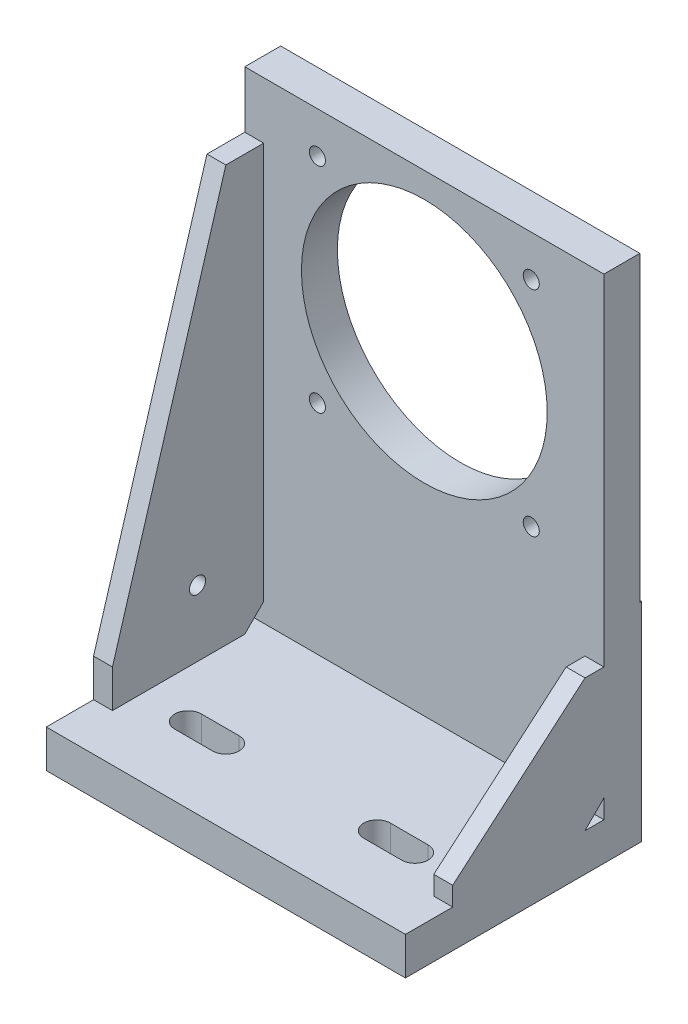
SolidWorks part; units mm, degrees
ref_plane "Front" through (0, 0, 0) normal (0, 0, 1) x (1, 0, 0)
ref_plane "Top" through (0, 0, 0) normal (0, 1, 0) x (1, 0, 0)
ref_plane "Right" through (0, 0, 0) normal (1, 0, 0) x (0, 0, -1)
sketch "Sketch1" plane through (0, 0, 0) normal (0, 1, 0) x (1, 0, 0)
  line L1 (0, 0) -> (190, 0)
  line L2 (0, 0) -> (0, -125)
  line L3 (0, -125) -> (190, -125)
  line L4 (190, 0) -> (190, -125)
  dimension "D1" = 190
  dimension "D2" = 125
extrude "Boss-Extrude1" add sketch "Sketch1" along normal blind 20
sketch "Sketch2" plane through (0, 0, 0) normal (0, 0, -1) x (-1, 0, 0)
  line L0 (-190, 0) -> (0, 0) construction
  line L1 (0, 20) -> (-190, 20)
  line L2 (0, 20) -> (0, 270)
  line L3 (0, 270) -> (-190, 270)
  line L4 (-190, 20) -> (-190, 270)
  dimension "D1" = 270
extrude "Boss-Extrude2" add sketch "Sketch2" against normal blind 20
sketch "Sketch3" plane through (0, 0, 0) normal (-1, 0, 0) x (0, 0, 1)
  line L1 (20, 20) -> (100, 20)
  line L2 (20, 20) -> (20, 240)
  line L3 (20, 240) -> (100, 240)
  line L4 (100, 20) -> (100, 240)
  dimension "D1" = 80
  dimension "D2" = 220
extrude "Boss-Extrude3" add sketch "Sketch3" against normal blind 10
sketch "Sketch4" plane through (190, 0, 0) normal (1, 0, 0) x (0, 0, -1)
  line L1 (-20, 20) -> (-100, 20)
  line L2 (-20, 20) -> (-20, 90)
  line L3 (-20, 90) -> (-100, 90)
  line L4 (-100, 20) -> (-100, 90)
  dimension "D1" = 80
  dimension "D2" = 70
extrude "Boss-Extrude4" add sketch "Sketch4" against normal blind 10
sketch "Sketch5" plane through (0, 0, 0) normal (-1, 0, 0) x (0, 0, 1)
  line L0 (20, 30) -> (20, 20)
  line L1 (20, 20) -> (30, 20)
  line L2 (30, 20) -> (20, 30)
  line L3 (20, 20) -> (100, 20) construction
  line L4 (20, 240) -> (20, 20) construction
  dimension "D1" = 10
extrude "Cut-Extrude1" cut sketch "Sketch5" against normal through all
sketch "Sketch6" plane through (0, 0, 0) normal (-1, 0, 0) x (0, 0, 1)
  line L0 (40, 240) -> (100, 40)
  line L1 (100, 240) -> (20, 240) construction
  line L2 (100, 20) -> (100, 240) construction
  line L3 (100, 40) -> (100, 240)
  line L4 (100, 240) -> (40, 240)
  line L5 (20, 240) -> (20, 270) construction
  line L6 (100, 20) -> (125, 20) construction
  dimension "D1" = 20
  dimension "D2" = 20
extrude "Cut-Extrude2" cut sketch "Sketch6" against normal up to surface (10 mm away) up to face at (10, 110, 54)
sketch "Sketch7" plane through (190, 0, 0) normal (1, 0, 0) x (0, 0, -1)
  line L0 (-100, 90) -> (-30, 90)
  line L1 (-20, 90) -> (-100, 90) construction
  line L2 (-30, 90) -> (-100, 30)
  line L3 (-100, 90) -> (-100, 20) construction
  line L4 (-100, 30) -> (-100, 90)
  line L5 (-20, 270) -> (-20, 90) construction
  line L6 (-125, 20) -> (-100, 20) construction
  dimension "D1" = 10
  dimension "D2" = 10
extrude "Cut-Extrude3" cut sketch "Sketch7" against normal up to surface (10 mm away) up to face at (180, 50, 54)
sketch "Sketch8" plane through (0, 0, 0) normal (0, 0, -1) x (-1, 0, 0)
  line L0 (0, 270) -> (0, 0) construction
  line L1 (-190, 270) -> (0, 270)
  line L2 (-190, 270) -> (-190, 110)
  line L3 (-190, 110) -> (0, 110)
  line L4 (0, 270) -> (0, 110)
  line L5 (-190, 0) -> (0, 0) construction
  dimension "D1" = 110
extrude "Cut-Extrude4" cut sketch "Sketch8" against normal blind 1
sketch "Sketch9" plane through (0, 0, 1) normal (0, 0, -1) x (-1, 0, 0)
  line L0 (-190, 0) -> (0, 0) construction
  line L1 (0, 110) -> (0, 0) construction
  circle A0 centre (-95, 191.7) radius 65
  dimension "D1" = 130
  dimension "D2" = 191.7
  dimension "D3" = 95
extrude "Cut-Extrude5" cut sketch "Sketch9" against normal through all
sketch "Sketch10" plane through (0, 20, 0) normal (0, 1, 0) x (1, 0, 0)
  line L0 (35, -85) -> (55, -85) construction
  line L1 (35, -78) -> (55, -78)
  line L2 (35, -92) -> (55, -92)
  line L3 (135, -85) -> (155, -85) construction
  line L4 (135, -78) -> (155, -78)
  line L5 (135, -92) -> (155, -92)
  line L7 (0, -20) -> (0, -1) construction
  line L8 (190, 0) -> (0, 0) construction
  arc A0 (35, -78) -> (35, -92) centre (35, -85) ccw
  arc A1 (55, -92) -> (55, -78) centre (55, -85) ccw
  arc A2 (135, -78) -> (135, -92) centre (135, -85) ccw
  arc A3 (155, -92) -> (155, -78) centre (155, -85) ccw
  point P2 (45, -85)
  point P7 (145, -85)
  dimension "D1" = 45
  dimension "D2" = 20
  dimension "D3" = 14
  dimension "D4" = 100
  dimension "D5" = 85
extrude "Cut-Extrude6" cut sketch "Sketch10" against normal through all
hole_wizard "M10x1.5 Tapped Hole1" positions "Sketch12" profile "Sketch11" tap size "M10x1.5" standard "JIS" end condition through all
sketch "Sketch12" plane through (0, 0, 1) normal (0, 0, -1) x (-1, 0, 0)
  line L0 (-38.4315, 248.2685) -> (-95, 191.7) construction
  line L1 (-95, 191.7) -> (-15, 191.7) construction
  line L3 (-95, 191.7) -> (-95, 271.7) construction
  circle A0 centre (-95, 191.7) radius 80 construction
  point P0 (-38.4315, 248.2685)
  point P19 (-151.5685, 248.2685)
  point P21 (-151.5685, 135.1315)
  point P23 (-38.4315, 135.1315)
  dimension "D1" = 45
  dimension "D2" = 160
sketch "Sketch11" plane through (38.4315, 248.2685, 1) normal (1, 0, 0) x (0, 1, 0)
  line L0 (0, 0) -> (0, 124)
  line L1 (0, 124) -> (4.25, 124)
  line L2 (4.25, 124) -> (4.25, 0)
  line L5 (4.25, 0) -> (0, 0)
  line L11 (0, -6.35) -> (0, 107.95) construction
  dimension "Thru Tap Drill Dia." = 8.5
  dimension "Thru Tap Drill Depth" = 124
cosmetic thread "Hole Thread1" parameters "D2"=10
cosmetic thread "Hole Thread2" parameters "D2"=10
cosmetic thread "Hole Thread3" parameters "D2"=10
cosmetic thread "Hole Thread4" parameters "D2"=10
hole_wizard "M10x1.5 Tapped Hole2" positions "Sketch14" profile "Sketch13" tap size "M10x1.5" standard "JIS"
sketch "Sketch14" plane through (0, 0, 0) normal (-1, 0, 0) x (0, 0, 1)
  line L0 (0, 0) -> (125, 0) construction
  line L1 (0, 110) -> (0, 0) construction
  point P0 (55, 55)
  dimension "D1" = 55
  dimension "D2" = 55
sketch "Sketch13" plane through (0, 55, 55) normal (0, 1, 0) x (0, 0, 1)
  line L0 (0, 0) -> (0, 10)
  line L1 (0, 10) -> (4.25, 10)
  line L2 (4.25, 10) -> (4.25, 0)
  line L5 (4.25, 0) -> (0, 0)
  line L11 (0, -6.35) -> (0, 107.95) construction
  dimension "Thru Tap Drill Dia." = 8.5
  dimension "Thru Tap Drill Depth" = 10
cosmetic thread "Hole Thread5" parameters "D2"=10
